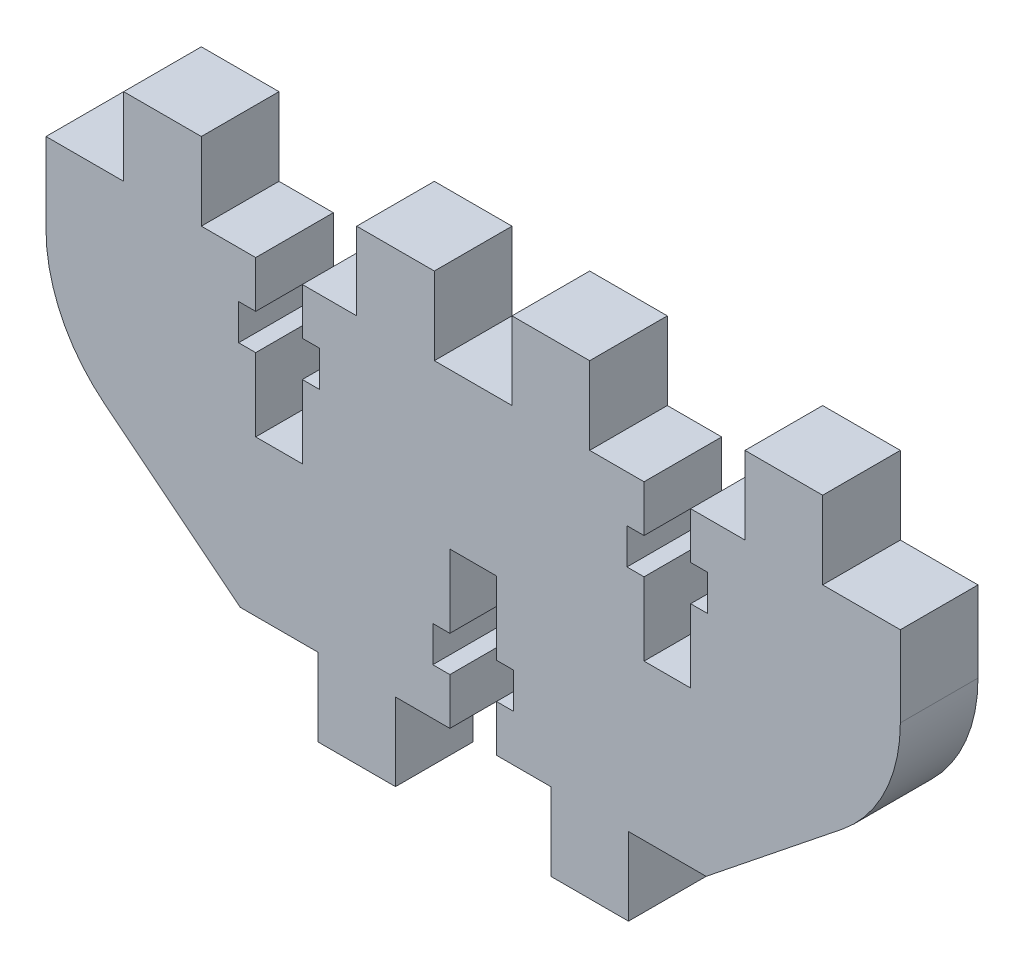
SolidWorks part; units mm, degrees
ref_plane "Plan de face" through (0, 0, 0) normal (0, 0, 1) x (1, 0, 0)
ref_plane "Plan de dessus" through (0, 0, 0) normal (0, 1, 0) x (1, 0, 0)
ref_plane "Plan de droite" through (0, 0, 0) normal (1, 0, 0) x (0, 0, -1)
sketch "Esquisse1" plane through (0, 0, 0) normal (0, 0, 1) x (1, 0, 0)
  line L0 (0, 0) -> (30.2829, 0) construction
  line L1 (0, 0) -> (0, -30.9586) construction
  line L2 (-10, 0) -> (-15, 0)
  line L3 (-27.5, 10) -> (-27.5, 20)
  line L4 (-15, 0) -> (-27.5, 10)
  line L5 (-2.5, 20) -> (2.5, 20)
  line L6 (10, 0) -> (15, 0)
  line L7 (15, 0) -> (27.5, 10)
  line L8 (27.5, 10) -> (27.5, 20)
  line L9 (27.5, 20) -> (22.5, 20)
  line L10 (-22.5, 20) -> (-27.5, 20)
  point P16 (0, 0)
  line B0 (-2.6, 3) -> (-2.6, 5.3)
  line B1 (1.5, 5.3) -> (1.5, 10)
  line B2 (-1.5, 10) -> (-1.5, 5.3)
  line B3 (-2.6, 5.3) -> (-1.5, 5.3)
  line B4 (0, 0) -> (0, 11.2208) construction
  line B5 (-1.5, 0) -> (-5, 0)
  line B6 (-5, -5) -> (-10, -5)
  line B7 (-10, -5) -> (-10, 0)
  line B8 (-5, -5) -> (-5, 0)
  line B9 (1.5, 0) -> (5, 0)
  line B10 (5, 0) -> (5, -5)
  line B11 (5, -5) -> (10, -5)
  line B12 (10, -5) -> (10, 0)
  line B13 (-1.5, 0) -> (1.5, 0) construction
  line B14 (1.5, 0) -> (1.5, 3)
  line B15 (1.5, 5.3) -> (2.6, 5.3)
  line B16 (2.6, 3) -> (1.5, 3)
  line B17 (1.5, 10) -> (-1.5, 10)
  line B18 (-1.5, 3) -> (-2.6, 3)
  line B19 (2.6, 5.3) -> (2.6, 3)
  line B20 (-1.5, 3) -> (-1.5, 0)
  line B21 (0, 10) -> (0, 0) construction
  line B22 (15.1, 17) -> (15.1, 14.7)
  line B23 (11, 14.7) -> (11, 10)
  line B24 (14, 10) -> (14, 14.7)
  line B25 (15.1, 14.7) -> (14, 14.7)
  line B26 (12.5, 20) -> (12.5, 8.7792) construction
  line B27 (14, 20) -> (17.5, 20)
  line B28 (17.5, 25) -> (22.5, 25)
  line B29 (22.5, 25) -> (22.5, 20)
  line B30 (17.5, 25) -> (17.5, 20)
  line B31 (11, 20) -> (7.5, 20)
  line B32 (7.5, 20) -> (7.5, 25)
  line B33 (7.5, 25) -> (2.5, 25)
  line B34 (2.5, 25) -> (2.5, 20)
  line B35 (14, 20) -> (11, 20) construction
  line B36 (11, 20) -> (11, 17)
  line B37 (11, 14.7) -> (9.9, 14.7)
  line B38 (9.9, 17) -> (11, 17)
  line B39 (11, 10) -> (14, 10)
  line B40 (14, 17) -> (15.1, 17)
  line B41 (9.9, 14.7) -> (9.9, 17)
  line B42 (14, 17) -> (14, 20)
  line B43 (12.5, 10) -> (12.5, 20) construction
  line B44 (-15.1, 17) -> (-15.1, 14.7)
  line B45 (-11, 14.7) -> (-11, 10)
  line B46 (-14, 10) -> (-14, 14.7)
  line B47 (-15.1, 14.7) -> (-14, 14.7)
  line B48 (-12.5, 20) -> (-12.5, 8.7792) construction
  line B49 (-14, 20) -> (-17.5, 20)
  line B50 (-17.5, 25) -> (-22.5, 25)
  line B51 (-22.5, 25) -> (-22.5, 20)
  line B52 (-17.5, 25) -> (-17.5, 20)
  line B53 (-11, 20) -> (-7.5, 20)
  line B54 (-7.5, 20) -> (-7.5, 25)
  line B55 (-7.5, 25) -> (-2.5, 25)
  line B56 (-2.5, 25) -> (-2.5, 20)
  line B57 (-14, 20) -> (-11, 20) construction
  line B58 (-11, 20) -> (-11, 17)
  line B59 (-11, 14.7) -> (-9.9, 14.7)
  line B60 (-9.9, 17) -> (-11, 17)
  line B61 (-11, 10) -> (-14, 10)
  line B62 (-14, 17) -> (-15.1, 17)
  line B63 (-9.9, 14.7) -> (-9.9, 17)
  line B64 (-14, 17) -> (-14, 20)
  line B65 (-12.5, 10) -> (-12.5, 20) construction
  dimension "D1" = 5
  dimension "D2" = 20
  dimension "D3" = 12.5
  dimension "D4" = 10
sketch_block_instance "Insert M3 plots ep 5mm-1"
sketch_block "Insert M3 plots ep 5mm" parameters "D1"=10, "D2"=5, "D3"=5
sketch_block_instance "Decoupe Insert M3-4"
sketch_block "Decoupe Insert M3" parameters "D1"=5.2, "D2"=3, "D3"=2.3, "D4"=3, "D5"=10
sketch_block_instance "Insert M3 plots ep 5mm-3"
sketch_block_instance "Insert M3 plots ep 5mm-4"
extrude "Boss.-Extru.1" add sketch "Esquisse1" along normal blind 5
fillet "Congé1" radius 10 2 edges at (-27.5, 10, 2.5) (27.5, 10, 2.5)
